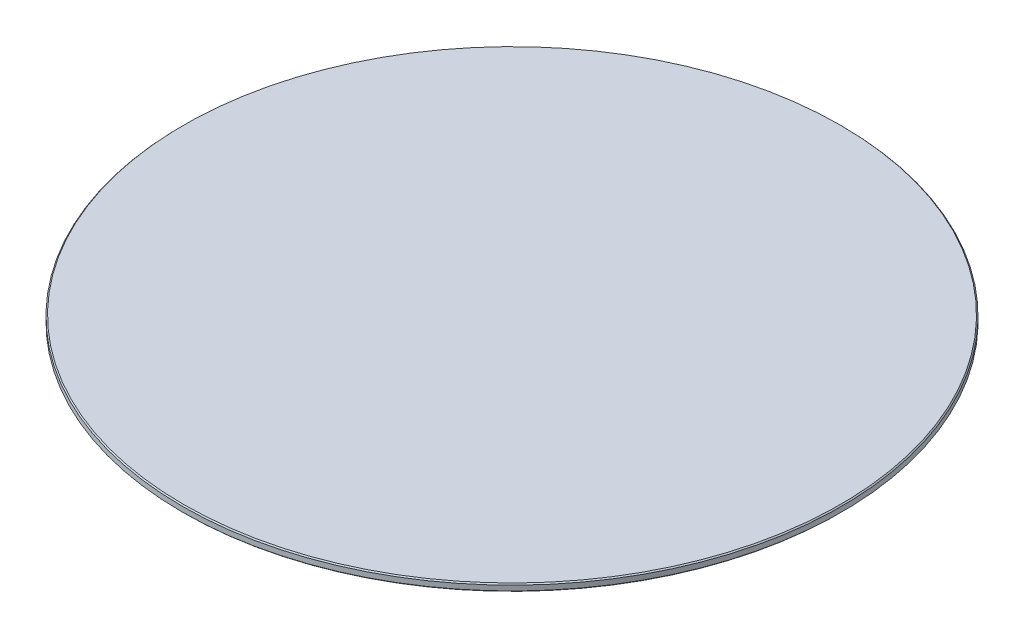
SolidWorks part; units mm, degrees
material "Glass"
ref_plane "Front Plane" through (0, 0, 0) normal (0, 0, 1) x (1, 0, 0)
ref_plane "Top Plane" through (0, 0, 0) normal (0, 1, 0) x (1, 0, 0)
ref_plane "Right Plane" through (0, 0, 0) normal (1, 0, 0) x (0, 0, -1)
sketch "Sketch1" plane through (0, 0, 0) normal (0, 1, 0) x (1, 0, 0)
  circle A0 centre (0, 0) radius 150
  dimension "D1" = 300
extrude "Boss-Extrude1" add sketch "Sketch1" along normal blind 3.3 contours A0
chamfer "Chamfer1" distance 0.5 angle 45 2 edges at (0, 0, 150) (0, 3.3, 150)
